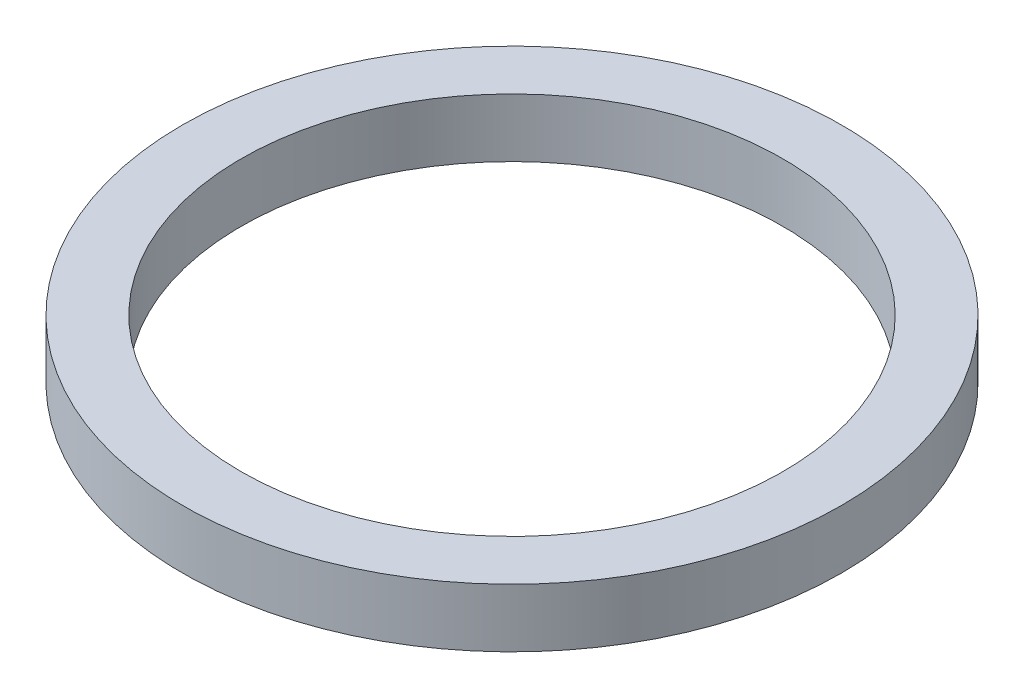
SolidWorks part; units mm, degrees
ref_plane "前基準面" through (0, 0, 0) normal (0, 0, 1) x (1, 0, 0)
ref_plane "上基準面" through (0, 0, 0) normal (0, 1, 0) x (1, 0, 0)
ref_plane "右基準面" through (0, 0, 0) normal (1, 0, 0) x (0, 0, -1)
sketch "草圖1" plane through (0, 0, 0) normal (0, 1, 0) x (1, 0, 0)
  circle A0 centre (0, 0) radius 234.95
  dimension "D1" = 469.9
extrude "伸長-薄件1" add sketch "草圖1" along normal blind 50.8 thin
